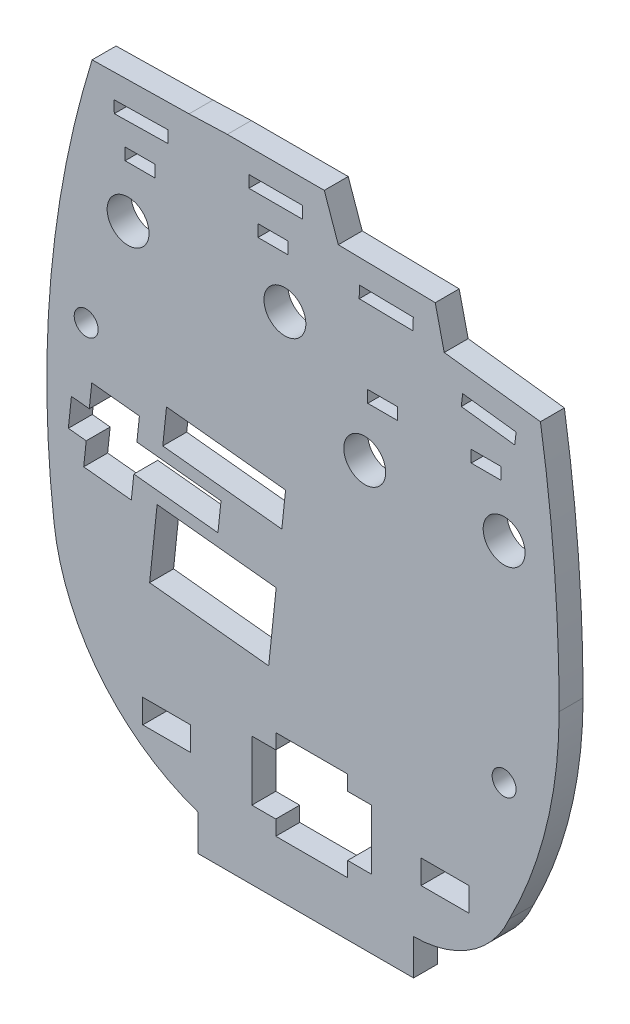
SolidWorks part; units mm, degrees
ref_plane "Front Plane" through (0, 0, 0) normal (0, 0, 1) x (1, 0, 0)
ref_plane "Top Plane" through (0, 0, 0) normal (0, 1, 0) x (1, 0, 0)
ref_plane "Right Plane" through (0, 0, 0) normal (1, 0, 0) x (0, 0, -1)
sketch "Sketch1" plane through (0, 0, 0) normal (0, 0, 1) x (1, 0, 0)
  line L0 (-4.5, 78.51) -> (-4.5, 76.51)
  line L1 (4.5, 78.51) -> (-4.5, 78.51)
  line L2 (-4.5, 76.51) -> (4.5, 76.51)
  line L3 (4.5, 76.51) -> (4.5, 78.51)
  line L4 (-4, -2.5) -> (0, -2.5)
  line L5 (0, 0) -> (18.54, 0) construction
  line L6 (0, 0) -> (0, 82.51) construction
  line L7 (12, 0) -> (0, 0)
  line L8 (0, 0) -> (-22.59, 0) construction
  line L9 (32.6473, 57.3216) -> (37.6473, 57.3216)
  line L10 (-12.9786, -18) -> (-12.9786, -24)
  line L11 (32.6473, 55.3216) -> (37.6473, 55.3216)
  line L12 (37.6473, 55.3216) -> (37.6473, 57.3216)
  line L13 (32.6473, 57.3216) -> (32.6473, 55.3216)
  line L14 (-27.02, 78.0626) -> (-18.0213, 78.2186)
  line L15 (-27.02, 78.0626) -> (-26.9853, 76.0629)
  line L16 (-26.9853, 76.0629) -> (-17.9866, 76.2189)
  line L17 (-17.9866, 76.2189) -> (-18.0213, 78.2186)
  line L18 (15.3631, 57.3216) -> (20.3631, 57.3216)
  line L19 (15.3631, 55.3216) -> (20.3631, 55.3216)
  line L20 (20.3631, 55.3216) -> (20.3631, 57.3216)
  line L21 (15.3631, 57.3216) -> (15.3631, 55.3216)
  line L22 (-2.9786, 72.1512) -> (2.0214, 72.1512)
  line L23 (13.9708, 71.7441) -> (13.9359, 69.7445)
  line L24 (13.9359, 69.7445) -> (22.9346, 69.5874)
  line L25 (-2.9786, 70.1512) -> (2.0214, 70.1512)
  line L26 (22.9695, 71.5871) -> (13.9708, 71.7441)
  line L27 (22.9346, 69.5874) -> (22.9695, 71.5871)
  line L28 (-22.59, 0) -> (-22.59, 82.14) construction
  line L29 (2.0214, 70.1512) -> (2.0214, 72.1512)
  line L30 (28.1404, 69.0671) -> (44.2196, 67.0929)
  line L31 (-2.9786, 72.1512) -> (-2.9786, 70.1512)
  line L32 (40.159, 63.5614) -> (31.226, 64.6582)
  line L33 (1.6326, 35.9121) -> (1.0057, 29.9449)
  line L34 (31.226, 64.6582) -> (30.9823, 62.6731)
  line L35 (-25.179, 72.1512) -> (-20.179, 72.1512)
  line L36 (18.54, 0) -> (18.54, 75.665) construction
  line L37 (0, 0) -> (36.18, 0) construction
  line L38 (-25.179, 70.1512) -> (-20.179, 70.1512)
  line L39 (30.9823, 62.6731) -> (39.9153, 61.5763)
  line L40 (-20.179, 70.1512) -> (-20.179, 72.1512)
  line L41 (-25.179, 72.1512) -> (-25.179, 70.1512)
  line L42 (39.9153, 61.5763) -> (40.159, 63.5614)
  line L43 (1.6326, 35.9121) -> (-18.2579, 38.0017)
  line L44 (0.0654, 20.9942) -> (-1.1883, 9.0599)
  line L45 (12, 0) -> (12, -2.5)
  line L46 (-18.8848, 32.0346) -> (1.0057, 29.9449)
  line L47 (12, -15) -> (0, -15)
  line L48 (-9.666, 24.0728) -> (-9.153, 28.9559)
  line L49 (-34.657, 26.6982) -> (-34.144, 31.5814)
  line L50 (-9.153, 28.9559) -> (-23.2057, 30.4322)
  line L51 (-32.0928, 22.4068) -> (-31.6749, 26.385)
  line L52 (-34.657, 26.6982) -> (-31.6749, 26.385)
  line L53 (-23.7187, 25.5491) -> (-9.666, 24.0728)
  line L54 (-23.2057, 30.4322) -> (-22.7877, 34.4103)
  line L55 (-24.1366, 21.571) -> (-32.0928, 22.4068)
  line L56 (-18.8848, 32.0346) -> (-18.2579, 38.0017)
  line L57 (-30.744, 35.2462) -> (-31.1619, 31.2681)
  line L58 (-22.7877, 34.4103) -> (-30.744, 35.2462)
  line L59 (-31.1619, 31.2681) -> (-34.144, 31.5814)
  line L60 (-24.1366, 21.571) -> (-23.7187, 25.5491)
  line L61 (-19.8251, 23.0838) -> (0.0654, 20.9942)
  line L62 (-21.0789, 11.1495) -> (-1.1883, 9.0599)
  line L63 (0, -15) -> (0, -12.5)
  line L64 (-4, -12.5) -> (-4, -2.5)
  line L65 (-19.8251, 23.0838) -> (-21.0789, 11.1495)
  line L66 (-12.9786, -24) -> (23.0214, -24)
  line L67 (-4, -12.5) -> (0, -12.5)
  line L68 (0, -2.5) -> (0, 0)
  line L69 (16, -12.5) -> (12, -12.5)
  line L70 (16, -12.5) -> (16, -2.5)
  line L71 (16, -2.5) -> (12, -2.5)
  line L72 (12, -12.5) -> (12, -15)
  line L73 (23.0214, -24) -> (23.0214, -18)
  line L74 (36.18, 0) -> (36.18, 68.08) construction
  line L75 (10.4412, 75.8064) -> (26.6388, 75.5236)
  line L76 (-8.1, 82.51) -> (8.1, 82.51)
  line L77 (-14.4912, 82.2805) -> (-30.6888, 81.9995)
  line L78 (28.1404, 69.0671) -> (26.6388, 75.5236)
  line L79 (-9.4095, 26.5144) -> (4.399, 25.0637) construction
  line L80 (39, -7.5) -> (16, -7.5) construction
  line L81 (10.4412, 75.8064) -> (8.1, 82.51)
  line L82 (-8.1, 82.51) -> (-14.4912, 82.2805)
  line L83 (-34.657, 26.6982) -> (47.343, 26.6982) construction
  line L84 (35.6925, 64.1098) -> (36.18, 68.08) construction
  line L85 (38.1473, 11.8216) -> (-37.0527, 11.8216) construction
  line L86 (-18.8848, 32.0346) -> (-19.8251, 23.0838) construction
  line L87 (-19.355, 27.5592) -> (-38.241, 29.5433) construction
  line L88 (18.4702, 71.6656) -> (18.54, 75.665) construction
  line L89 (-22.5206, 78.1406) -> (-22.59, 82.14) construction
  line L90 (0, 78.51) -> (0, 82.51) construction
  line L91 (38.1473, 46.8216) -> (38.1473, 11.8216) construction
  arc A0 (23.0214, -18) -> (39, -7.5) centre (23.0214, -0.592) ccw
  circle A1 centre (38.1473, 11.8216) radius 2
  arc A2 (-37.0527, 11.8216) -> (-30.6888, 81.9995) centre (130.7995, 31.9779) cw
  circle A3 centre (-24.679, 61.6512) radius 3.5
  circle A4 centre (1.5214, 61.6512) radius 3.5
  circle A5 centre (14.8631, 46.8216) radius 3.5
  circle A6 centre (38.1473, 46.8216) radius 3.5
  arc A7 (-37.0527, 11.8216) -> (-12.9786, -18) centre (-1.2138, 16.1253) ccw
  circle A8 centre (-31.6815, 43.4564) radius 2
  circle A9 centre (-14, -9.1244) radius 2 construction
  arc A10 (47.343, 26.6982) -> (39, -7.5) centre (-26.9181, 26.6982) cw
  arc A11 (47.343, 26.6982) -> (44.2196, 67.0929) centre (-215.4276, 26.6982) ccw
  dimension "D1" = 7
  dimension "D15" = 22.59
  dimension "D16" = 82.14
  dimension "D21" = 18
  dimension "D22" = 14.8631
  dimension "D23" = 68.08
  dimension "D24" = 4
  dimension "D27" = 5
  dimension "D28" = 23.0214
  dimension "D29" = 55.3216
  dimension "D30" = 32.6473
  dimension "D39" = 25.179
  dimension "D40" = 9.153
  dimension "D41" = 9.666
  dimension "D42" = 12.9786
  dimension "D43" = 14
  dimension "D44" = 35
  dimension "D47" = 57.3216
  dimension "D48" = 4
  dimension "D65" = 61.6512
  dimension "D72" = 9.1244
  dimension "D61" = 46.8216
  dimension "D62" = 2
  dimension "D53" = 9.0001
  dimension "D2" = 4
  dimension "D8" = 12
  dimension "D14" = 10
  dimension "D9" = 9
  dimension "D10" = 1.0057
  dimension "D11" = 1.5214
  dimension "D12" = 6
  dimension "D13" = 82.51
  dimension "D17" = 18.54
  dimension "D18" = 2.5
  dimension "D19" = 75.665
  dimension "D20" = 36.18
  dimension "D25" = 4
  dimension "D26" = 16.2
  dimension "D32" = 15.3631
  dimension "D33" = 70.1512
  dimension "D34" = 8.1
  dimension "D35" = 38.1473
  dimension "D36" = 2.9786
  dimension "D37" = 4
  dimension "D38" = 4.91
  dimension "D45" = 20
  dimension "D46" = 4
  dimension "D49" = 4.5
  dimension "D50" = 24.679
  dimension "D51" = 25.1285
  dimension "D52" = 31.6815
  dimension "D54" = 8
  dimension "D56" = 14.13
  dimension "D57" = 72.1512
  dimension "D59" = 21.571
  dimension "D60" = 43.4564
  dimension "ThumbLinkLengthMCP" = 18.99
extrude "Boss-Extrude1" add sketch "Sketch1" along normal blind 4
sketch "Sketch2" plane through (0, 0, 0) normal (0, 0, -1) x (-1, 0, 0)
  line L0 (-5.0214, -24) -> (-5.0214, -5.2587) construction
  line L1 (-24.2714, -10) -> (-32.2714, -10)
  line L2 (-32.2714, -10) -> (-32.2714, -6)
  line L3 (-32.2714, -6) -> (-24.2714, -6)
  line L4 (-24.2714, -6) -> (-24.2714, -10)
  line L5 (12.9786, -24) -> (-23.0214, -24) construction
  line L6 (14.2286, -6) -> (14.2286, -10)
  line L7 (22.2286, -6) -> (14.2286, -6)
  line L8 (22.2286, -10) -> (22.2286, -6)
  line L9 (14.2286, -10) -> (22.2286, -10)
  dimension "D1" = 4
  dimension "D2" = 8
  dimension "D3" = 19.25
  dimension "D4" = 14
extrude "Cut-Extrude1" cut sketch "Sketch2" against normal through all
equation "\"D13@Sketch1\"= \"HL@parametersSketch@prostheticParameters.SLDPRT\" * 0.446'Middle Base Frame"
equation "\"D15@Sketch1\"= \"HB@parametersSketch@prostheticParameters.SLDPRT\" * 0.251'Index Base Frame X"
equation "\"D16@Sketch1\"= \"HL@parametersSketch@prostheticParameters.SLDPRT\" * 0.444'Index Base Frame Y"
equation "\"D17@Sketch1\"= \"HB@parametersSketch@prostheticParameters.SLDPRT\" * 0.206'Ring Base Frame X"
equation "\"D19@Sketch1\"= \"HL@parametersSketch@prostheticParameters.SLDPRT\" * 0.409'Ring base Frame Y"
equation "\"D20@Sketch1\"= \"HB@parametersSketch@prostheticParameters.SLDPRT\" * 0.402'Pinky Base Frame X"
equation "\"D23@Sketch1\"= \"HL@parametersSketch@prostheticParameters.SLDPRT\" * 0.368'Pinky Base Frame Y"
equation "\"D26@Sketch1\"= \"fingerWidth@parametersSketch@prostheticParameters.SLDPRT\"'Fingers Width"
equation "\"D59@Sketch1\"= \"HL@parametersSketch@prostheticParameters.SLDPRT\" * 0.1166'Hole Thumb Y"
equation "\"D40@Sketch1\"= \"HB@parametersSketch@prostheticParameters.SLDPRT\" * 0.1017'Hole Thumb X1"
equation "\"D41@Sketch1\"= \"HB@parametersSketch@prostheticParameters.SLDPRT\" * 0.1074'Hole Thumb X2"
equation "\"ThumbLinkLengthMCP@Sketch1\"= \"HB@parametersSketch@prostheticParameters.SLDPRT\" * 0.211"
equation "\"D53@Sketch1\"= \"fingerWidth@parametersSketch@prostheticParameters.SLDPRT\" * 0.55556"
equation "\"D34@Sketch1\"= \"fingerWidth@parametersSketch@prostheticParameters.SLDPRT\" / 2"
